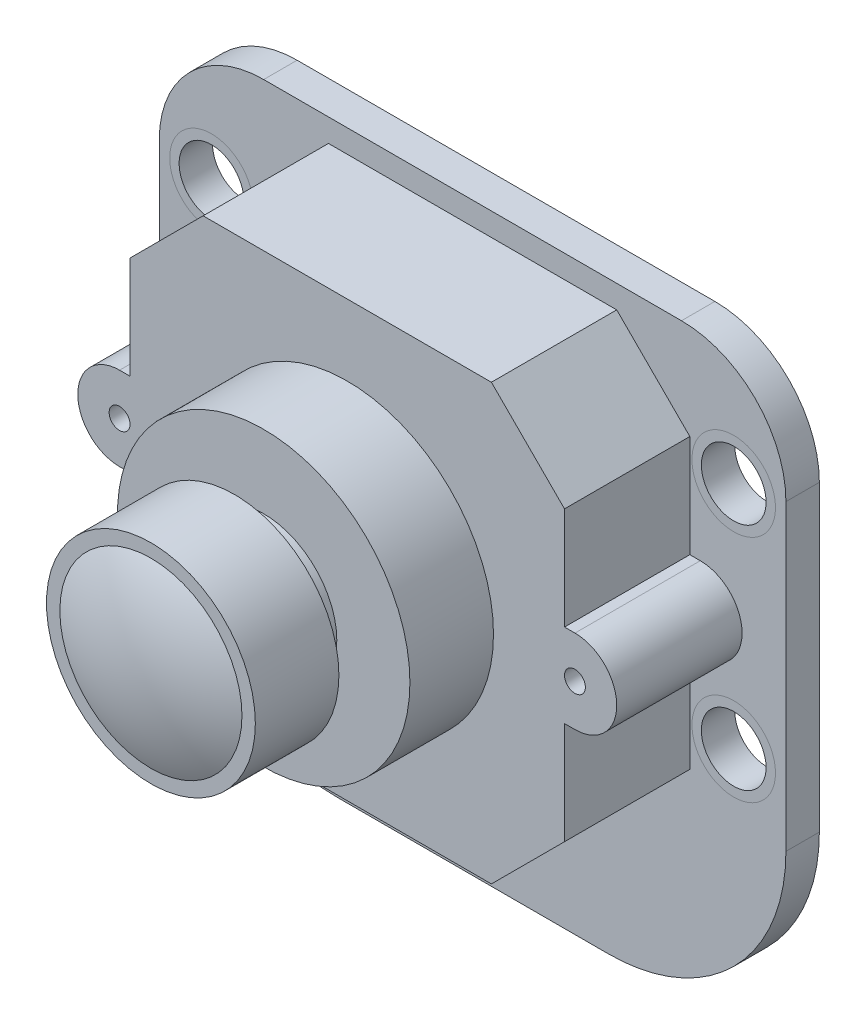
SolidWorks part; units mm, degrees
ref_plane "前视基准面" through (0, 0, 0) normal (0, 0, 1) x (1, 0, 0)
ref_plane "上视基准面" through (0, 0, 0) normal (0, 1, 0) x (1, 0, 0)
ref_plane "右视基准面" through (0, 0, 0) normal (1, 0, 0) x (0, 0, -1)
sketch "草图1" plane through (0, 0, 0) normal (0, 0, 1) x (1, 0, 0)
  line L0 (0, 14) -> (0, -14) construction
  line L1 (-15, -14) -> (15, -14)
  line L2 (-15, -14) -> (-15, 14)
  line L3 (-15, 14) -> (15, 14)
  line L4 (15, -14) -> (15, 14)
  line L5 (-15, -14) -> (15, 14) construction
  line L6 (-15, 14) -> (15, -14) construction
  circle A0 centre (10, 9) radius 5
  circle A1 centre (6.5, -5.5) radius 8.5
  circle A2 centre (-6.5, -5.5) radius 8.5
  circle A3 centre (-10, 9) radius 5
  point P0 (0, 0)
  dimension "D3" = 10
  dimension "D4" = 17
  dimension "D1" = 28
  dimension "D2" = 30
sketch "草图3" plane through (0, 0, 0) normal (0, 0, 1) x (1, 0, 0)
  line L0 (0, 14) -> (0, -14) construction
  line L4 (-15, -14) -> (15, -14)
  line L5 (15, -14) -> (15, 14)
  line L6 (15, 14) -> (-15, 14)
  line L7 (-15, 14) -> (-15, -14)
  line L8 (-6.5, -14) -> (6.5, -14)
  line L9 (15, -5.5) -> (15, 9)
  line L10 (10, 14) -> (-10, 14)
  line L11 (-15, 9) -> (-15, -5.5)
  circle A0 centre (12.5, 8.5) radius 1.55
  circle A1 centre (-10, 9) radius 5
  arc A2 (-10, 14) -> (-15, 9) centre (-10, 9) ccw
  circle A3 centre (-6.5, -5.5) radius 8.5
  arc A4 (-15, -5.5) -> (-6.5, -14) centre (-6.5, -5.5) ccw
  circle A5 centre (6.5, -5.5) radius 8.5
  arc A6 (6.5, -14) -> (15, -5.5) centre (6.5, -5.5) ccw
  circle A7 centre (10, 9) radius 5
  arc A8 (15, 9) -> (10, 14) centre (10, 9) ccw
  circle A9 centre (12.5, -2.5) radius 1.55
  circle A10 centre (-12.5, -2.5) radius 1.55
  circle A11 centre (-12.5, 8.5) radius 1.55
  dimension "D6" = 3.1
  dimension "D7" = 3.1
  dimension "D8" = 11
  dimension "D9" = 25
  dimension "D10" = 11.5
  dimension "D1" = 0
  dimension "D2" = 0
  dimension "D3" = 0
  dimension "D4" = 0
  dimension "D5" = 0
extrude "凸台-拉伸1" add sketch "草图3" along normal blind 1.6
sketch "草图4" plane through (0, 0, 1.6) normal (0, 0, 1) x (1, 0, 0)
  line L0 (0, 14) -> (0, -14) construction
  line L1 (10, 14) -> (-10, 14) construction
  line L2 (-6.5, -14) -> (6.5, -14) construction
  line L3 (15, 2.5) -> (-15, 2.5) construction
  line L4 (15, -5.5) -> (15, 9) construction
  line L5 (-15, 9) -> (-15, -5.5) construction
  line L6 (-10.4, 9.4) -> (-6.9, 12.9)
  line L7 (-6.9, -7.9) -> (6.9, -7.9)
  line L8 (-10.4, -4.4) -> (-10.4, 0.5)
  line L9 (-6.9, 12.9) -> (6.9, 12.9)
  line L10 (10.4, -4.4) -> (10.4, 0.5)
  line L11 (-10.4, -7.9) -> (10.4, 12.9) construction
  line L12 (-10.4, 12.9) -> (10.4, -7.9) construction
  line L13 (6.9, 12.9) -> (10.4, 9.4)
  line L14 (6.9, -7.9) -> (10.4, -4.4)
  line L15 (-10.4, -4.4) -> (-6.9, -7.9)
  line L16 (10.9, 0.5) -> (10.4, 0.5)
  line L17 (10.9, 4.5) -> (10.4, 4.5)
  line L18 (10.4, 4.5) -> (10.4, 9.4)
  line L19 (-10.9, 4.5) -> (-10.4, 4.5)
  line L20 (-10.9, 0.5) -> (-10.4, 0.5)
  line L21 (-10.4, 4.5) -> (-10.4, 9.4)
  arc A0 (10.9, 0.5) -> (10.9, 4.5) centre (10.9, 2.5) ccw
  arc A1 (-10.9, 0.5) -> (-10.9, 4.5) centre (-10.9, 2.5) cw
  circle A2 centre (10.9, 2.5) radius 0.5
  circle A3 centre (-10.9, 2.5) radius 0.5
  point P12 (0, 2.5)
  dimension "D4" = 4
  dimension "D10" = 1
  dimension "D11" = 1
  dimension "D1" = 11.5
  dimension "D2" = 20.8
  dimension "D3" = 20.8
  dimension "D5" = 2.5
extrude "凸台-拉伸2" add sketch "草图4" along normal blind 6
sketch "草图5" plane through (0, 0, 7.6) normal (0, 0, 1) x (1, 0, 0)
  circle A0 centre (0, 2.5) radius 7
  dimension "D1" = 14
extrude "凸台-拉伸3" add sketch "草图5" along normal blind 4
sketch "草图6" plane through (0, 0, 11.6) normal (0, 0, 1) x (1, 0, 0)
  circle A0 centre (0, 2.5) radius 3.5
  dimension "D1" = 7
extrude "凸台-拉伸4" add sketch "草图6" along normal blind 1.4
sketch "草图7" plane through (0, 0, 13) normal (0, 0, 1) x (1, 0, 0)
  circle A0 centre (0, 2.5) radius 5
  dimension "D1" = 10
extrude "凸台-拉伸5" add sketch "草图7" along normal blind 4
ref_plane "基准面1" through (0, 2.5, 0) normal (0, 1, 0) x (1, 0, 0)
sketch "草图8" plane through (0, 2.5, 0) normal (0, 1, 0) x (1, 0, 0)
  line L0 (0, -17) -> (0, -21.2545) construction
  line L1 (-5, -17) -> (5, -17) construction
  line L2 (0, -17) -> (-4.3589, -17)
  line L3 (0, -17) -> (0, -18)
  arc A0 (-4.3589, -17) -> (0, -18) centre (0, -8) ccw
  dimension "D2" = 20
  dimension "D1" = 1
revolve "旋转1" add sketch "草图8" angle 360 about L0
sketch "草图9" plane through (0, 0, 1.6) normal (0, 0, 1) x (1, 0, 0)
  line L0 (0, 14) -> (0, 0) construction
  line L1 (10, 14) -> (-10, 14) construction
  circle A0 centre (-12.5, 8.5) radius 2
  circle A1 centre (-12.5, -2.5) radius 2
  circle A2 centre (12.5, -2.5) radius 2
  circle A3 centre (12.5, 8.5) radius 2
  dimension "D1" = 4
  dimension "D2" = 4
split line "分割线1"
sketch "草图10" plane through (0, 0, 0) normal (1, 0, 0) x (0, 0, -1)
  line L0 (-1.6, 2.5) -> (-18, 2.5) construction
  line L1 (-1.6, -5.5) -> (-1.6, 9) construction
  line L2 (-14.9607, 2.5) -> (-22.8553, 19.4299)
  line L3 (-17, 7.5) -> (-17, -2.5) construction
  arc A0 (-17, 6.8589) -> (-17, -1.8589) centre (-8, 2.5) ccw construction
  point P9 (-17, 6.8732)
  dimension "D1" = 65
surface "曲面-旋转1" sketch "草图10" parameters "D1"=360
